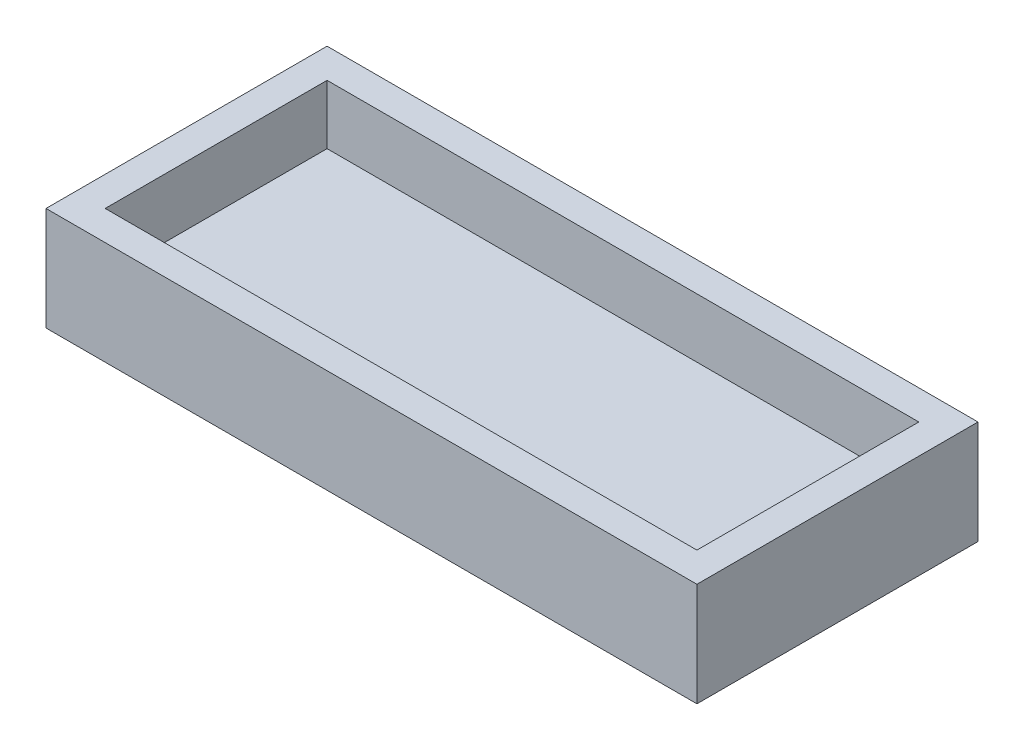
SolidWorks part; units mm, degrees
ref_plane "Front Plane" through (0, 0, 0) normal (0, 0, 1) x (1, 0, 0)
ref_plane "Top Plane" through (0, 0, 0) normal (0, 1, 0) x (1, 0, 0)
ref_plane "Right Plane" through (0, 0, 0) normal (1, 0, 0) x (0, 0, -1)
sketch "Sketch1" plane through (0, 0, 0) normal (0, 1, 0) x (1, 0, 0)
  line L1 (-20, 7.5) -> (20, 7.5)
  line L2 (-20, 7.5) -> (-20, -7.5)
  line L3 (-20, -7.5) -> (20, -7.5)
  line L4 (20, 7.5) -> (20, -7.5)
  line L5 (-20, 7.5) -> (20, -7.5) construction
  line L6 (-20, -7.5) -> (20, 7.5) construction
  point P0 (0, 0)
extrude "Boss-Extrude1" add sketch "Sketch1" along normal blind 3
sketch "Sketch2" plane through (0, 0, 0) normal (0, -1, 0) x (1, 0, 0)
  line L0 (-20, -7.5) -> (-20, 7.5) construction
  line L1 (20, -7.5) -> (-20, -7.5)
  line L2 (20, -7.5) -> (20, 7.5)
  line L3 (20, 7.5) -> (-20, 7.5)
  line L4 (-20, -7.5) -> (-20, 7.5)
  line L9 (22, -9.5) -> (22, 9.5)
  line L14 (22, 9.5) -> (-22, 9.5)
  line L15 (-22, -9.5) -> (-22, 9.5)
  line L16 (22, -9.5) -> (-22, -9.5)
  dimension "D2" = 2
extrude "Boss-Extrude2" add sketch "Sketch2" against normal offset from surface (7 mm away) 4 up to face at (0, 3, 0) offset beyond the face yes
